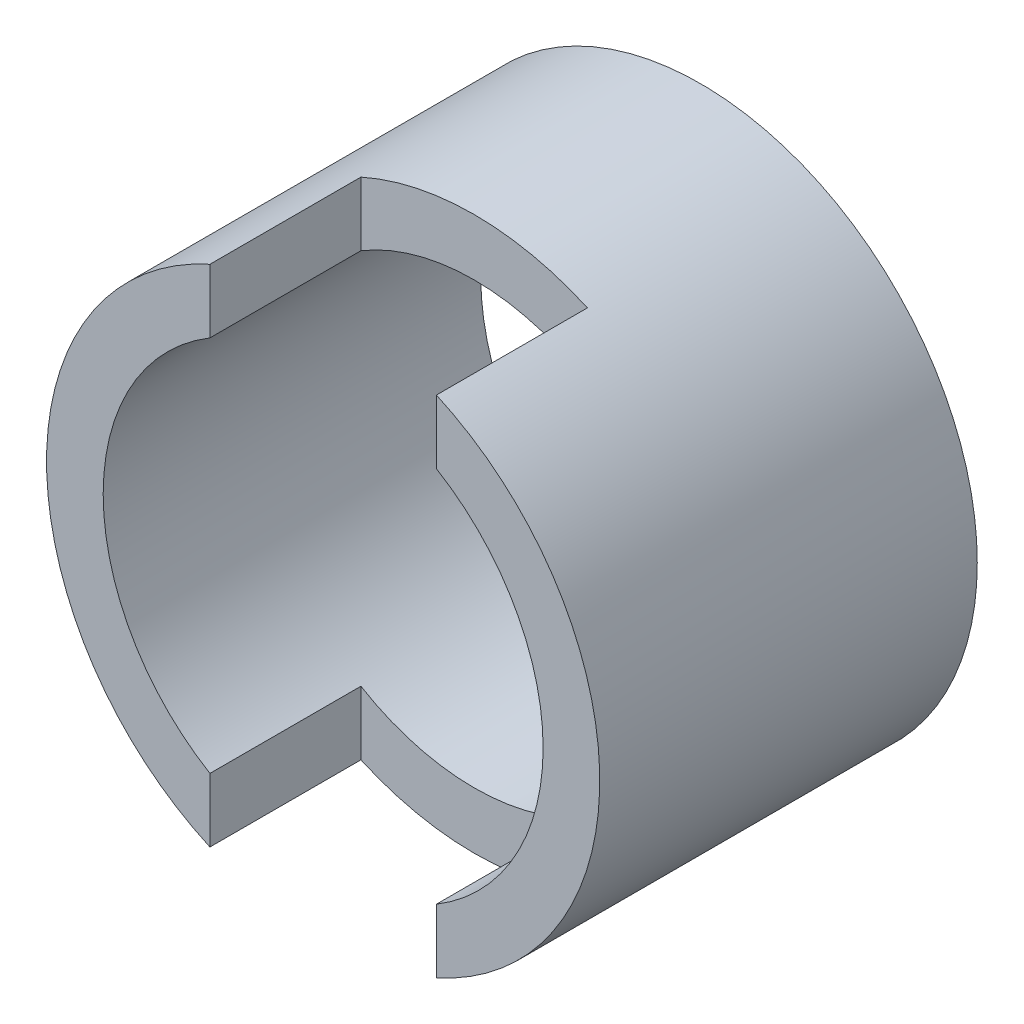
SolidWorks part; units mm, degrees
material "ABS"
ref_plane "Front Plane" through (0, 0, 0) normal (0, 0, 1) x (1, 0, 0)
ref_plane "Top Plane" through (0, 0, 0) normal (0, 1, 0) x (1, 0, 0)
ref_plane "Right Plane" through (0, 0, 0) normal (1, 0, 0) x (0, 0, -1)
sketch "Sketch1" plane through (0, 0, 0) normal (0, 0, 1) x (1, 0, 0)
  circle A0 centre (0, 0) radius 18.5
  circle A1 centre (0, 0) radius 23.2625
  dimension "D1" = 37
  dimension "D2" = 4.7625
extrude "Boss-Extrude1" add sketch "Sketch1" along normal blind 31.75
sketch "Sketch2" plane through (0, 0, 31.75) normal (0, 0, 1) x (1, 0, 0)
  line L1 (-9.525, 25.4) -> (9.525, 25.4)
  line L2 (-9.525, 25.4) -> (-9.525, -25.4)
  line L3 (-9.525, -25.4) -> (9.525, -25.4)
  line L4 (9.525, 25.4) -> (9.525, -25.4)
  line L5 (0, -25.4) -> (0, 25.4) construction
  line L6 (-9.525, 0) -> (9.525, 0) construction
  point P0 (0, 0)
  dimension "D1" = 19.05
  dimension "D2" = 50.8
extrude "Cut-Extrude1" cut sketch "Sketch2" against normal blind 12.7
